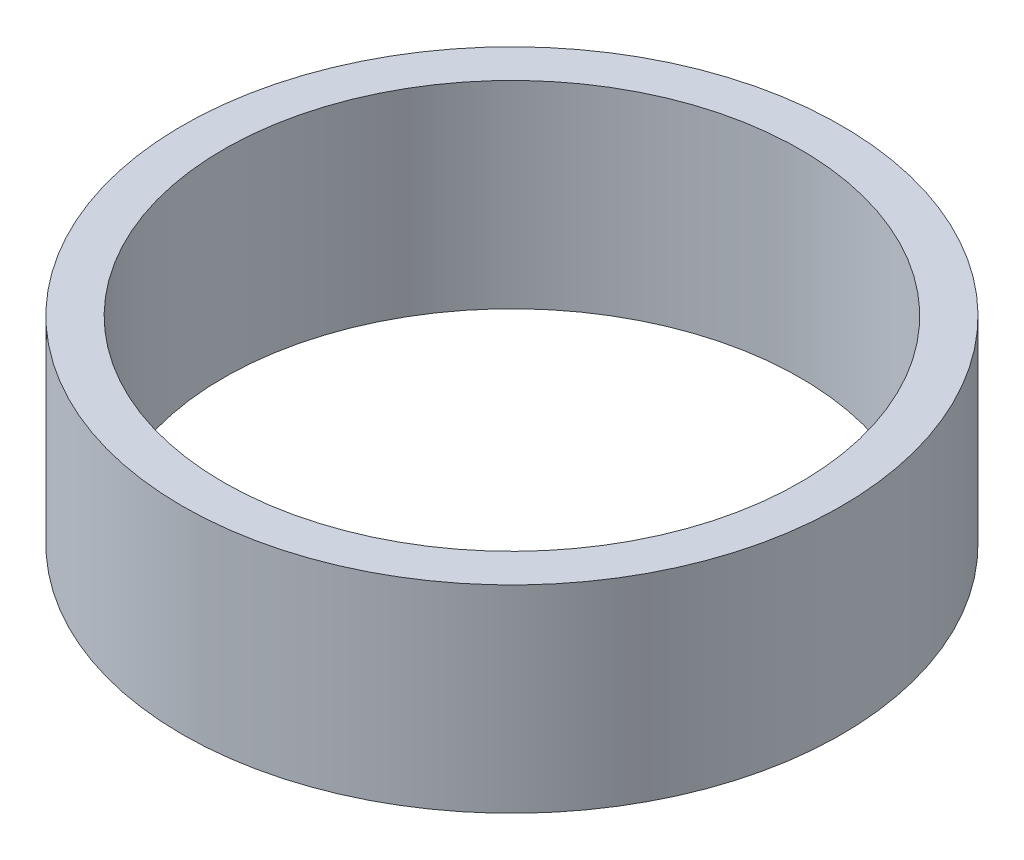
SolidWorks part; units mm, degrees
ref_plane "前视基准面" through (0, 0, 0) normal (0, 0, 1) x (1, 0, 0)
ref_plane "上视基准面" through (0, 0, 0) normal (0, 1, 0) x (1, 0, 0)
ref_plane "右视基准面" through (0, 0, 0) normal (1, 0, 0) x (0, 0, -1)
other "Configuration Table"
sketch "草图1" plane through (0, 0, 0) normal (0, 1, 0) x (1, 0, 0)
  circle A0 centre (0, 0) radius 20
  circle A1 centre (0, 0) radius 17.5
  dimension "D1" = 35
  dimension "D2" = 40
extrude "凸台-拉伸1" add sketch "草图1" along normal blind 12
